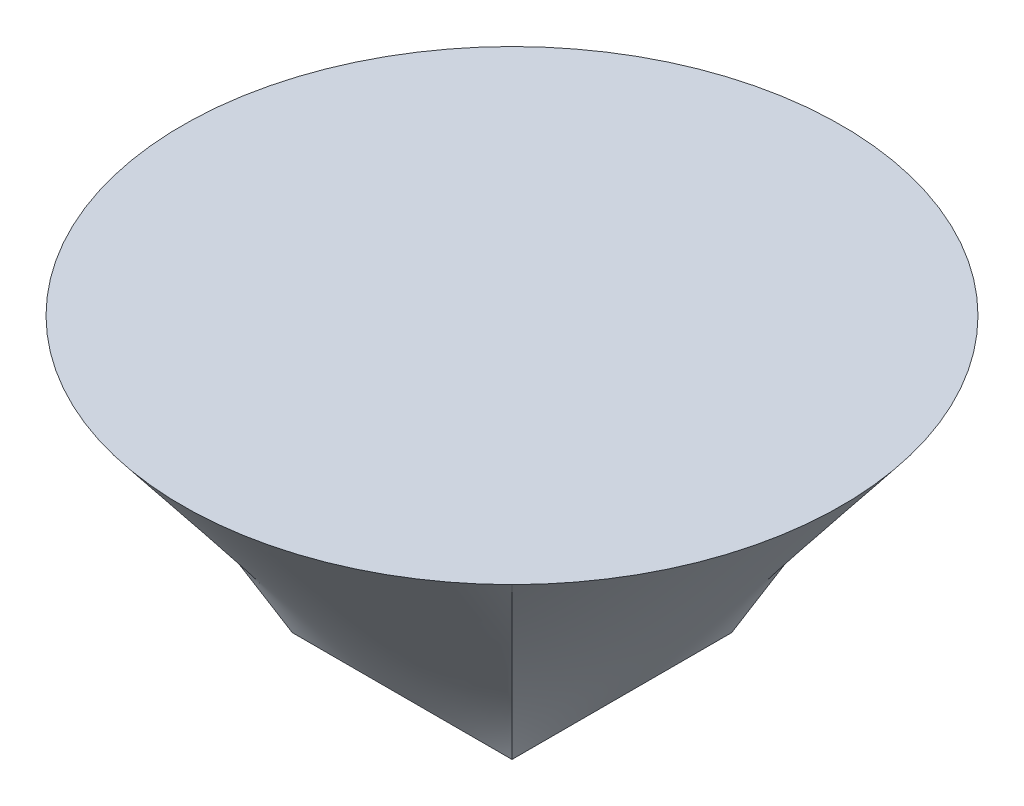
SolidWorks part; units mm, degrees
ref_plane "Plano frontal" through (0, 0, 0) normal (0, 0, 1) x (1, 0, 0)
ref_plane "Plano superior" through (0, 0, 0) normal (0, 1, 0) x (1, 0, 0)
ref_plane "Plano direito" through (0, 0, 0) normal (1, 0, 0) x (0, 0, -1)
sketch "Esboço1" plane through (0, 0, 0) normal (0, 1, 0) x (1, 0, 0)
  line L1 (-20, -20) -> (20, -20)
  line L2 (-20, -20) -> (-20, 20)
  line L3 (-20, 20) -> (20, 20)
  line L4 (20, -20) -> (20, 20)
  line L5 (-20, -20) -> (20, 20) construction
  line L6 (-20, 20) -> (20, -20) construction
  point P0 (0, 0)
  dimension "D1" = 40
ref_plane "Plano1" through (0, 50, 0) normal (0, 1, 0) x (1, 0, 0)
sketch "Esboço3" plane through (0, 50, 0) normal (0, 1, 0) x (1, 0, 0)
  line L0 (-60, 0) -> (60, 0) construction
  line L1 (-42.2014, 42.6502) -> (42.6502, -42.2014) construction
  line L2 (0, 0) -> (20, 0) construction
  line L3 (20, -20) -> (20, 20) construction
  circle A0 centre (0, 0) radius 60
  point P3 (-42.2014, 42.6502)
  point P6 (0, 0)
  point P9 (0.2244, 0.2244)
  point P13 (-60, 0)
  dimension "D1" = 120
  dimension "D2" = 45
  dimension "D3" = 45
loft "Loft4" add profiles "Esboço1", "Esboço3"
